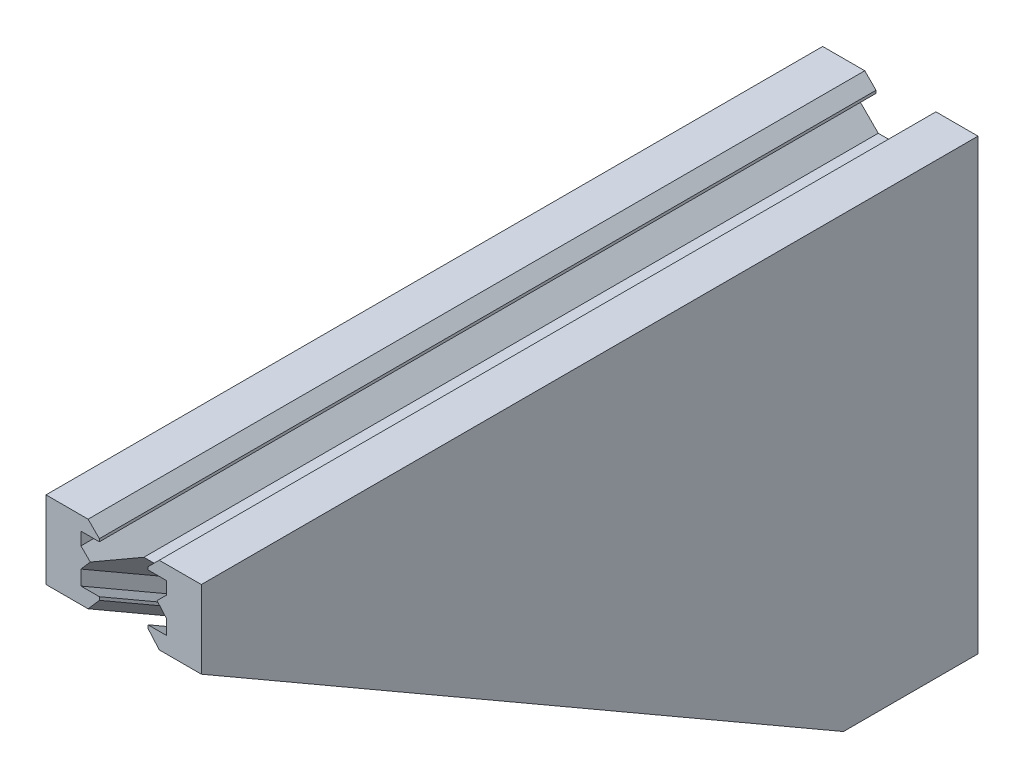
SolidWorks part; units mm, degrees
ref_plane "Top" through (0, 0, 0) normal (0, 0, 1) x (1, 0, 0)
ref_plane "Front" through (0, 0, 0) normal (0, 1, 0) x (1, 0, 0)
ref_plane "Right" through (0, 0, 0) normal (1, 0, 0) x (0, 0, -1)
sketch "Profile Sketch" plane through (0, -25.3242, 100.8753) normal (1, 0, 0) x (0, 1, 0)
  line L0 (-42.4108, -100.8753) -> (15.3242, -0.8753)
  line L2 (25.3242, -100.8753) -> (-42.4108, -100.8753)
  line L3 (15.3242, -0.8753) -> (25.3242, -0.8753)
  line L4 (25.3242, -0.8753) -> (25.3242, -100.8753)
  dimension "D1" = 60
  dimension "D2" = 100
  dimension "D3" = 10
extrude "Profile Extrude" add sketch "Profile Sketch" along normal blind 20 from offset 10 offset against normal yes
ref_plane "Interface Perpendicular Plane" through (0, 40.8013, 70.6699) normal (0, 0.5, 0.866) x (-1, 0, 0)
sketch "Top T-Nut Slot Sketch" plane through (0, 0, 100) normal (0, 0, 1) x (1, 0, 0)
  line L0 (0, 0) -> (0, -10) construction
  line L1 (10, 0) -> (-10, 0) construction
  line L2 (10, -10) -> (-10, -10) construction
  line L3 (-4.58, 0) -> (-3.13, -1.45)
  line L4 (-3.13, -1.45) -> (-3.13, -1.8)
  line L5 (-3.13, -1.8) -> (-5.5, -1.8)
  line L6 (-5.5, -1.8) -> (-5.5, -3.44)
  line L7 (-5.5, -3.44) -> (-2.84, -6.1)
  line L8 (-2.84, -6.1) -> (2.84, -6.1)
  line L9 (-4.58, 0) -> (4.58, 0)
  line L11 (5.5, -3.44) -> (2.84, -6.1)
  line L12 (5.5, -1.8) -> (5.5, -3.44)
  line L13 (3.13, -1.8) -> (5.5, -1.8)
  line L14 (3.13, -1.45) -> (3.13, -1.8)
  line L15 (4.58, 0) -> (3.13, -1.45)
  point P15 (0, -6.1)
  dimension "D1" = 3.13
  dimension "D2" = 45
  dimension "D3" = 1.45
  dimension "D4" = 1.64
  dimension "D5" = 5.5
  dimension "D6" = 6.1
  dimension "D7" = 1.8
extrude "Top T-Nut Slot Cut" cut sketch "Top T-Nut Slot Sketch" against normal through all
chamfer "Front Edge Chamfer" distance 10 angle 90 1 edges at (0, -67.735, 0)
sketch "Front T-Nut Slot Sketch" plane through (20, 44.2491, 68.6792) normal (0, 0.5, 0.866) x (-1, 0, 0)
  line L0 (20, 62.6415) -> (20, 42.7427) construction
  line L3 (15.42, 62.6415) -> (16.87, 61.1915)
  line L4 (16.87, 61.1915) -> (16.87, 60.8415)
  line L5 (16.87, 60.8415) -> (14.5, 60.8415)
  line L6 (14.5, 60.8415) -> (14.5, 59.2015)
  line L7 (14.5, 59.2015) -> (17.16, 56.5415)
  line L8 (17.16, 56.5415) -> (22.84, 56.5415)
  line L9 (15.42, 62.6415) -> (24.58, 62.6415)
  line L11 (25.5, 59.2015) -> (22.84, 56.5415)
  line L12 (25.5, 60.8415) -> (25.5, 59.2015)
  line L13 (23.13, 60.8415) -> (25.5, 60.8415)
  line L14 (23.13, 61.1915) -> (23.13, 60.8415)
  line L15 (24.58, 62.6415) -> (23.13, 61.1915)
  line L17 (10, 62.6415) -> (30, 62.6415) construction
  point P15 (20, 56.5415)
  point P24 (20, 62.6415)
  point P25 (20, 62.6415)
  dimension "D1" = 3.13
  dimension "D2" = 45
  dimension "D3" = 1.45
  dimension "D4" = 1.64
  dimension "D5" = 5.5
  dimension "D6" = 6.1
  dimension "D7" = 1.8
extrude "Front T-Nut Slot Cut" cut sketch "Front T-Nut Slot Sketch" along normal through all and the other way up to vertex (95.4701 mm away) other way up to point (10, -57.735, 17.3205)
equation "\"Interface Angle\"= 60deg"
equation "\"D1@Profile Sketch\"=\"Interface Angle\""
